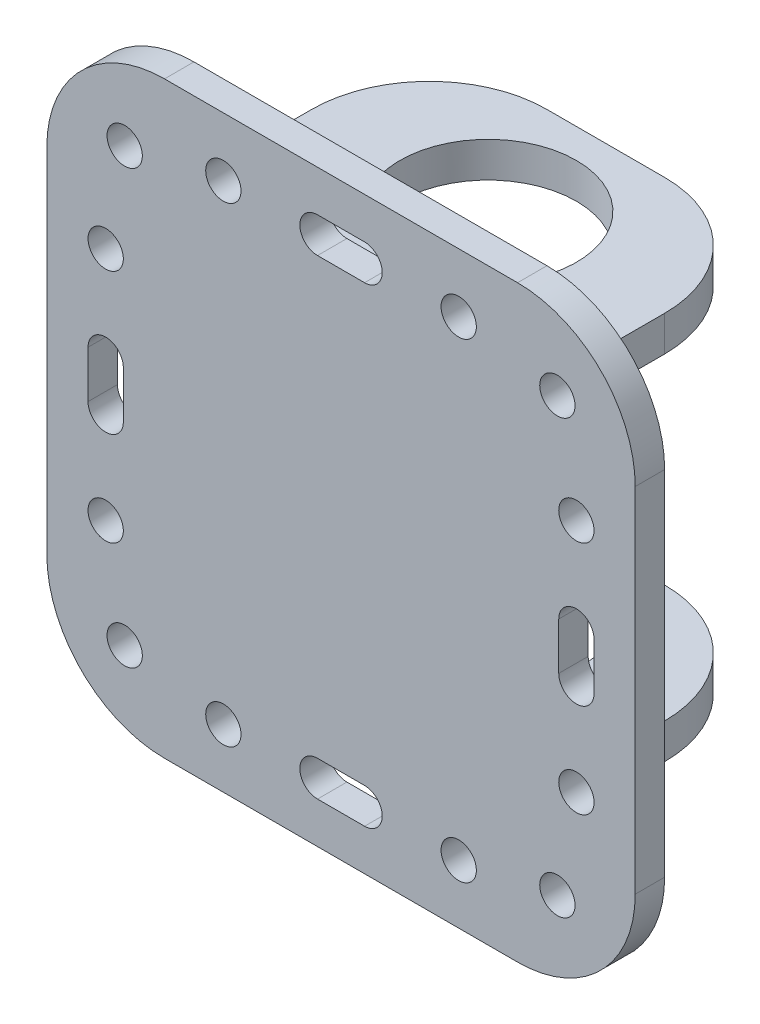
SolidWorks part; units mm, degrees
ref_plane "前视基准面" through (0, 0, 0) normal (0, 0, 1) x (1, 0, 0)
ref_plane "上视基准面" through (0, 0, 0) normal (0, 1, 0) x (1, 0, 0)
ref_plane "右视基准面" through (0, 0, 0) normal (1, 0, 0) x (0, 0, -1)
other "Configuration Table"
sketch "Sketch1" plane through (0, 0, 0) normal (0, 0, 1) x (1, 0, 0)
  line L1 (-25, -25) -> (25, -25)
  line L2 (-25, -25) -> (-25, 25)
  line L3 (-25, 25) -> (25, 25)
  line L4 (25, -25) -> (25, 25)
  line L5 (-25, -25) -> (25, 25) construction
  line L6 (-25, 25) -> (25, -25) construction
  point P0 (0, 0)
  dimension "D1" = 50
  dimension "D2" = 50
extrude "Boss-Extrude1" add sketch "Sketch1" along normal blind 2.5
sketch "Sketch2" plane through (0, 0, 0) normal (0, 0, -1) x (-1, 0, 0)
  line L0 (0, 0) -> (0, 20) construction
  line L1 (0, 0) -> (5.8312, 0) construction
  line L2 (-2, 20) -> (2, 20) construction
  line L3 (-2, 21.5) -> (2, 21.5)
  line L4 (-2, 18.5) -> (2, 18.5)
  line L5 (20, 2) -> (20, -2) construction
  line L8 (21.5, 2) -> (21.5, -2)
  line L11 (18.5, 2) -> (18.5, -2)
  line L14 (2, -20) -> (-2, -20) construction
  line L17 (2, -21.5) -> (-2, -21.5)
  line L18 (2, -18.5) -> (-2, -18.5)
  line L19 (-20, -2) -> (-20, 2) construction
  line L20 (-21.5, -2) -> (-21.5, 2)
  line L21 (-18.5, -2) -> (-18.5, 2)
  line L22 (0, 0) -> (18.3848, 18.3848) construction
  line L23 (0, 0) -> (16.2673, 0) construction
  line L24 (0, 0) -> (0, 12.7025) construction
  line L25 (18.5, 0) -> (21.5, 0) construction
  line L26 (21.5, 0) -> (20, 0) construction
  line L27 (20, 0) -> (20, 10) construction
  line L28 (0, 21.5) -> (0, 18.5) construction
  line L29 (0, 18.5) -> (0, 20) construction
  line L30 (0, 20) -> (10, 20) construction
  arc A0 (-2, 21.5) -> (-2, 18.5) centre (-2, 20) ccw
  arc A1 (2, 18.5) -> (2, 21.5) centre (2, 20) ccw
  circle A3 centre (0, 0) radius 12.5 construction
  arc A11 (21.5, 2) -> (18.5, 2) centre (20, 2) ccw
  arc A12 (18.5, -2) -> (21.5, -2) centre (20, -2) ccw
  arc A13 (2, -21.5) -> (2, -18.5) centre (2, -20) ccw
  arc A14 (-2, -18.5) -> (-2, -21.5) centre (-2, -20) ccw
  arc A15 (-21.5, -2) -> (-18.5, -2) centre (-20, -2) ccw
  arc A16 (-18.5, 2) -> (-21.5, 2) centre (-20, 2) ccw
  circle A17 centre (18.3848, 18.3848) radius 1.5
  circle A18 centre (18.3848, -18.3848) radius 1.5
  circle A19 centre (-18.3848, -18.3848) radius 1.5
  circle A20 centre (-18.3848, 18.3848) radius 1.5
  circle A21 centre (20, 10) radius 1.5
  circle A22 centre (20, -10) radius 1.5
  circle A23 centre (-20, -10) radius 1.5
  circle A24 centre (-20, 10) radius 1.5
  circle A25 centre (10, 20) radius 1.5
  circle A26 centre (-10, 20) radius 1.5
  circle A27 centre (10, -20) radius 1.5
  circle A28 centre (-10, -20) radius 1.5
  point P5 (0, 20)
  point P15 (20, 0)
  point P18 (-5.1576, -3.854)
  point P24 (0, -20)
  point P31 (-20, 0)
  point P36 (0, 0)
  point P40 (-5.1586, -3.854)
  dimension "D1" = 1.5
  dimension "D4" = 25
  dimension "D7" = 3
  dimension "D9" = 3
  dimension "D11" = 3
  dimension "D2" = 4
  dimension "D3" = 20
  dimension "D6" = 45
  dimension "D8" = 26
  dimension "D10" = 10
  dimension "D12" = 10
  dimension "D5" = 4
extrude "Cut-Extrude1" cut sketch "Sketch2" against normal blind 5
fillet "Fillet1" radius 10 4 edges at (-25, 25, 1.25) (25, 25, 1.25) (25, -25, 1.25) (-25, -25, 1.25)
sketch "Sketch3" plane through (0, 0, 0) normal (0, 0, -1) x (-1, 0, 0)
  line L0 (0, 0) -> (0, 15) construction
  line L1 (0, 0) -> (13.305, 0) construction
  line L2 (-15, -16.5) -> (15, -13.5) construction
  line L3 (-15, 13.5) -> (15, 13.5)
  line L4 (-15, 13.5) -> (-15, 16.5)
  line L5 (-15, 16.5) -> (15, 16.5)
  line L6 (15, 13.5) -> (15, 16.5)
  line L7 (-15, 13.5) -> (15, 16.5) construction
  line L8 (-15, 16.5) -> (15, 13.5) construction
  line L9 (-15, -13.5) -> (15, -16.5) construction
  line L10 (15, -13.5) -> (15, -16.5)
  line L11 (-15, -16.5) -> (15, -16.5)
  line L12 (-15, -13.5) -> (-15, -16.5)
  line L13 (-15, -13.5) -> (15, -13.5)
  dimension "D1" = 3
  dimension "D2" = 30
  dimension "D3" = 15
extrude "Boss-Extrude2" add sketch "Sketch3" along normal blind 20
sketch "Sketch4" plane through (0, -16.5, 0) normal (0, -1, 0) x (1, 0, 0)
  line L0 (0, 0) -> (0, -20) construction
  line L1 (15, -20) -> (-15, -20) construction
  line L2 (0, -20) -> (0, -10) construction
  circle A0 centre (0, -10) radius 7.5
  dimension "D1" = 15
extrude "Cut-Extrude2" cut sketch "Sketch4" against normal through all
fillet "Fillet2" radius 10 4 edges at (-15, 15, -20) (15, 15, -20) (15, -15, -20) (-15, -15, -20)
